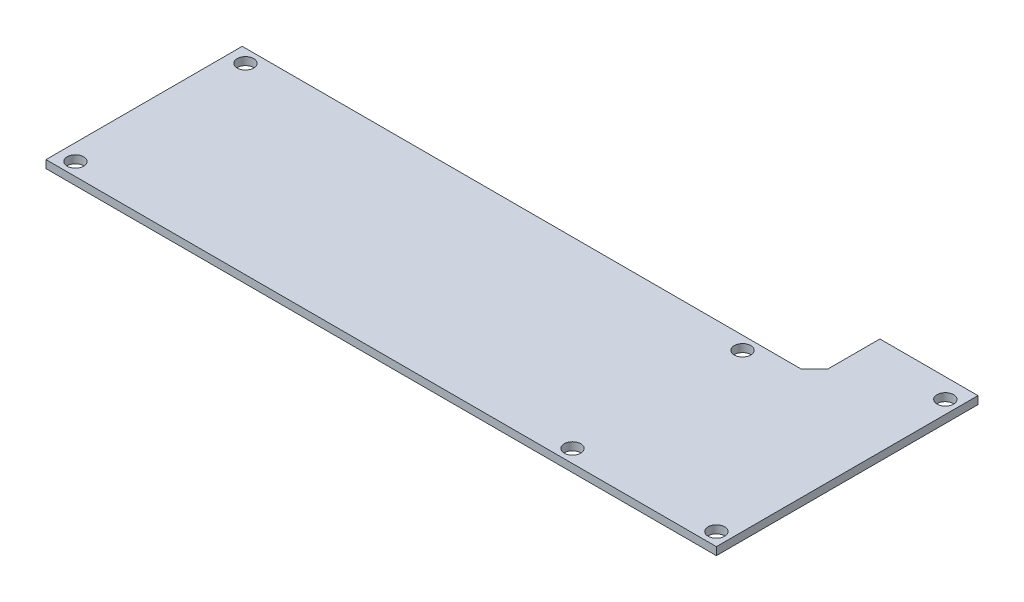
SolidWorks part; units mm, degrees
ref_plane "Front Plane" through (0, 0, 0) normal (0, 0, 1) x (1, 0, 0)
ref_plane "Top Plane" through (0, 0, 0) normal (0, 1, 0) x (1, 0, 0)
ref_plane "Right Plane" through (0, 0, 0) normal (1, 0, 0) x (0, 0, -1)
sketch "Sketch1" plane through (0, 0, 0) normal (0, 1, 0) x (1, 0, 0)
  line L1 (-65.0875, -25.4) -> (65.0875, -25.4)
  line L2 (-65.0875, -25.4) -> (-65.0875, 25.4)
  line L3 (-65.0875, 25.4) -> (65.0875, 25.4)
  line L4 (65.0875, -25.4) -> (65.0875, 25.4)
  line L5 (-65.0875, -25.4) -> (65.0875, 25.4) construction
  line L6 (-65.0875, 25.4) -> (65.0875, -25.4) construction
  point P0 (0, 0)
  dimension "D1" = 130.175
  dimension "D2" = 50.8
extrude "Boss-Extrude1" add sketch "Sketch1" along normal blind 1.524
sketch "Sketch6" plane through (0, 1.524, 0) normal (0, 1, 0) x (1, 0, 0)
  line L1 (-65.0875, 12.7) -> (46.0375, 12.7)
  line L2 (-65.0875, 12.7) -> (-65.0875, 25.4)
  line L3 (-65.0875, 25.4) -> (46.0375, 25.4)
  line L4 (46.0375, 12.7) -> (46.0375, 25.4)
  line L5 (-65.0875, 25.4) -> (-65.0875, -25.4) construction
  line L7 (65.0875, 25.4) -> (-65.0875, 25.4) construction
  line L8 (65.0875, -25.4) -> (65.0875, 25.4) construction
  dimension "D1" = 19.05
  dimension "D2" = 12.7
extrude "Cut-Extrude1" cut sketch "Sketch6" against normal up to next
chamfer "Chamfer2" distance 2.54 angle 45 1 edges at (46.0375, 0.762, -12.7)
sketch "Sketch7" plane through (0, 1.524, 0) normal (0, 1, 0) x (1, 0, 0)
  line L1 (65.0875, 25.4) -> (46.0375, 25.4) construction
  line L2 (65.0875, -25.4) -> (65.0875, 25.4) construction
  circle A0 centre (53.6575, 17.78) radius 1.5
  circle A1 centre (53.6575, 5.08) radius 1.5
  circle A2 centre (28.2575, 2.54) radius 1.5
  circle A3 centre (10.4775, 2.54) radius 1.5
  circle A4 centre (-7.3025, 2.54) radius 1.5
  circle A5 centre (-25.0825, 2.54) radius 1.5
  circle A6 centre (-42.8625, 2.54) radius 1.5
  circle A7 centre (-60.6425, 2.54) radius 1.5
  dimension "D1" = 3
  dimension "D4" = 20.32
  dimension "D7" = 17.78
  dimension "D8" = 17.78
  dimension "D9" = 17.78
  dimension "D10" = 17.78
  dimension "D11" = 17.78
  dimension "D6" = 36.83
  dimension "D2" = 11.43
  dimension "D3" = 7.62
  dimension "D5" = 22.86
sketch "Sketch8" plane through (0, 1.524, 0) normal (0, 1, 0) x (1, 0, 0)
  line L0 (-15.9844, -10.16) -> (27.366, -10.16) construction
  line L1 (-6.0325, -3.0475) -> (-6.0325, -14.0015) construction
  line L3 (65.0875, 25.4) -> (46.0375, 25.4) construction
  line L4 (65.0875, -25.4) -> (65.0875, 25.4) construction
  dimension "D1" = 71.12
  dimension "D2" = 35.56
hole_wizard "Ø3.2 (3.2) Diameter Hole1" positions "Sketch10" profile "Sketch9" hole size "Ø3.2" standard "Ansi Metric" end condition up to next
sketch "Sketch10" plane through (0, 1.524, 0) normal (0, 1, 0) x (-1, 0, 0)
  line L0 (-65.0875, 25.4) -> (-65.0875, -25.4) construction
  line L1 (-65.0875, -25.4) -> (-46.0375, -25.4) construction
  point P0 (-62.5475, 22.86)
  point P1 (-62.5475, -21.59)
  point P3 (-34.6075, 22.86)
  point P5 (-34.6075, -10.16)
  point P7 (61.9125, 22.86)
  point P9 (61.9125, -10.16)
  dimension "D1" = 2.54
  dimension "D2" = 3.81
  dimension "D3" = 2.54
  dimension "D4" = 48.26
  dimension "D5" = 15.24
  dimension "D6" = 30.48
  dimension "D7" = 30.48
  dimension "D8" = 48.26
  dimension "D9" = 127
  dimension "D10" = 15.24
  dimension "D11" = 127
  dimension "D12" = 48.26
sketch "Sketch9" plane through (62.5475, 1.524, 22.86) normal (1, 0, 0) x (0, 0, 1)
  line L0 (0, 0) -> (0, 1.524)
  line L1 (0, 1.524) -> (1.6, 1.524)
  line L2 (1.6, 1.524) -> (1.6, 0)
  line L5 (1.6, 0) -> (0, 0)
  line L11 (0, -6.35) -> (0, 107.95) construction
  dimension "Thru Hole Dia." = 3.2
  dimension "Thru Hole Depth" = 1.524
